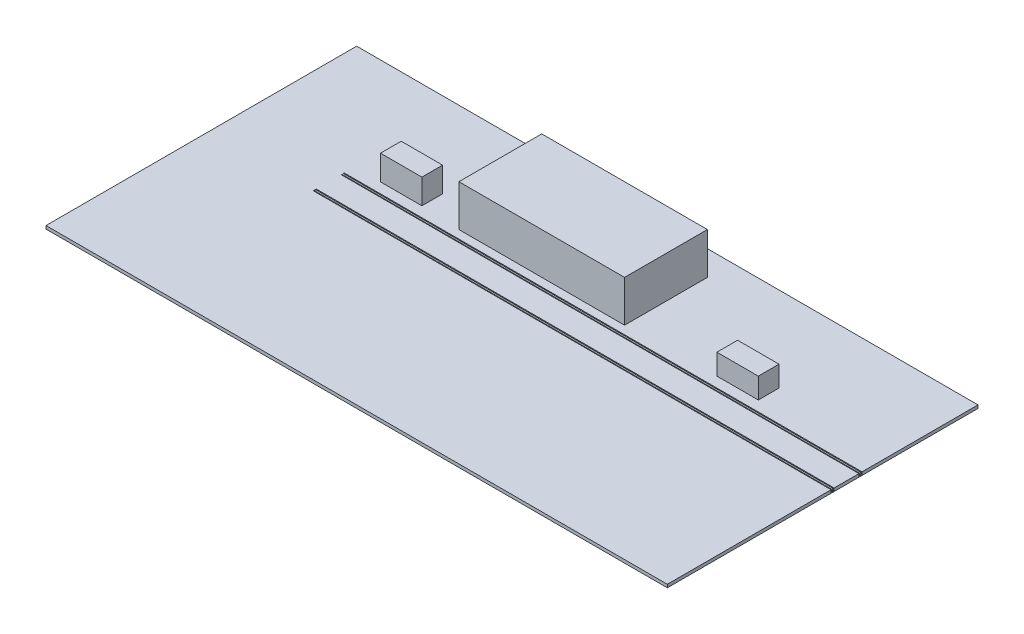
SolidWorks part; units mm, degrees
ref_plane "Front Plane" through (0, 0, 0) normal (0, 0, 1) x (1, 0, 0)
ref_plane "Top Plane" through (0, 0, 0) normal (0, 1, 0) x (1, 0, 0)
ref_plane "Right Plane" through (0, 0, 0) normal (1, 0, 0) x (0, 0, -1)
sketch "Sketch1" plane through (0, 0, 0) normal (0, 1, 0) x (1, 0, 0)
  line L1 (0, 0) -> (30000, 0)
  line L2 (0, 0) -> (0, 15000)
  line L3 (0, 15000) -> (30000, 15000)
  line L4 (30000, 0) -> (30000, 15000)
  dimension "D1" = 30000
  dimension "D2" = 15000
extrude "Boss-Extrude3" add sketch "Sketch1" along normal blind 150
ref_plane "Plane1" through (5000, 0, 0) normal (-1, 0, 0) x (0, 0, 1)
sketch "Sketch3" plane through (5000, 0, 0) normal (-1, 0, 0) x (0, 0, 1)
  line L0 (-15000, 150) -> (0, 150) construction
  line L1 (-9400, 150) -> (-7904, 150)
  line L2 (-9400, 150) -> (-9400, 0)
  line L3 (-9400, 0) -> (-7904, 0)
  line L4 (-7904, 150) -> (-7904, 0)
  line L5 (-15000, 0) -> (0, 0) construction
  line L7 (-9385.7322, 9.9989) -> (-9344.9003, 22.6122)
  line L8 (-9337.8517, 32.1667) -> (-9337.8517, 85.4861)
  line L9 (-9345.6022, 95.2298) -> (-9374.9273, 102)
  line L10 (-9374.9273, 102) -> (-9366.7893, 137.2495)
  line L11 (-9357.0456, 145) -> (-9294.9544, 145)
  line L12 (-9285.2107, 137.2495) -> (-9277.0727, 102)
  line L13 (-9314.1483, 85.4861) -> (-9314.1483, 32.1017)
  line L14 (-9307.1803, 22.5725) -> (-9266.1873, 9.5293)
  line L16 (-9306.3978, 95.2298) -> (-9277.0727, 102)
  line L17 (-9326, 145) -> (-9326, 0) construction
  line L18 (-10531.7423, 0) -> (-8120.2577, 0) construction
  line L19 (-9252, 150) -> (-9252, 0)
  line L20 (-15000, 150) -> (-15000, 0) construction
  line L21 (-8052, 150) -> (-8052, 0)
  line L22 (-8652, 150) -> (-8652, 0) construction
  line L23 (-7997.6022, 95.2298) -> (-8026.9273, 102)
  line L24 (-7996.8197, 22.5725) -> (-8037.8127, 9.5293)
  line L25 (-7918.2678, 9.9989) -> (-7959.0997, 22.6122)
  line L26 (-7966.1483, 32.1667) -> (-7966.1483, 85.4861)
  line L27 (-7989.8517, 85.4861) -> (-7989.8517, 32.1017)
  line L28 (-7958.3978, 95.2298) -> (-7929.0727, 102)
  line L29 (-8018.7893, 137.2495) -> (-8026.9273, 102)
  line L30 (-7946.9544, 145) -> (-8009.0456, 145)
  line L31 (-7929.0727, 102) -> (-7937.2107, 137.2495)
  arc A0 (-9266.1873, 9.5293) -> (-9259.2193, 0) centre (-9269.2193, 0) cw
  arc A1 (-9392.7708, 0) -> (-9385.7322, 9.9989) centre (-9382.7807, 0.4443) cw
  arc A2 (-9314.1483, 32.1017) -> (-9307.1803, 22.5725) centre (-9304.1483, 32.1017) ccw
  arc A3 (-9337.8517, 32.1667) -> (-9344.9003, 22.6122) centre (-9347.8517, 32.1667) cw
  arc A4 (-9294.9544, 145) -> (-9285.2107, 137.2495) centre (-9294.9544, 135) cw
  arc A5 (-9357.0456, 145) -> (-9366.7893, 137.2495) centre (-9357.0456, 135) ccw
  arc A6 (-9314.1483, 85.4861) -> (-9306.3978, 95.2298) centre (-9304.1483, 85.4861) cw
  arc A7 (-9337.8517, 85.4861) -> (-9345.6022, 95.2298) centre (-9347.8517, 85.4861) ccw
  arc A8 (-8037.8127, 9.5293) -> (-8044.7807, 0) centre (-8034.7807, 0) ccw
  arc A9 (-7989.8517, 32.1017) -> (-7996.8197, 22.5725) centre (-7999.8517, 32.1017) cw
  arc A10 (-7911.2292, 0) -> (-7918.2678, 9.9989) centre (-7921.2193, 0.4443) ccw
  arc A11 (-7966.1483, 32.1667) -> (-7959.0997, 22.6122) centre (-7956.1483, 32.1667) ccw
  arc A12 (-7989.8517, 85.4861) -> (-7997.6022, 95.2298) centre (-7999.8517, 85.4861) ccw
  arc A13 (-7966.1483, 85.4861) -> (-7958.3978, 95.2298) centre (-7956.1483, 85.4861) cw
  arc A14 (-7946.9544, 145) -> (-7937.2107, 137.2495) centre (-7946.9544, 135) cw
  arc A15 (-8009.0456, 145) -> (-8018.7893, 137.2495) centre (-8009.0456, 135) ccw
  point P16 (-15000, 75)
  point P31 (-9259.2193, 7.3122)
  point P34 (-9392.7807, 7.3122)
  point P37 (-9314.1483, 24.7895)
  point P40 (-9337.8517, 24.7895)
  point P43 (-9287, 145)
  point P46 (-9365, 145)
  point P49 (-9314.1483, 93.4404)
  point P52 (-9337.8517, 93.4404)
  point P59 (-8044.7807, 7.3122)
  point P64 (-7989.8517, 24.7895)
  point P70 (-7911.2193, 7.3122)
  point P72 (-7966.1483, 24.7895)
  point P77 (-7989.8517, 93.4404)
  point P81 (-7966.1483, 93.4404)
  point P89 (-8017, 145)
  point P90 (-7939, 145)
  dimension "D9" = 10
  dimension "D1" = 1496
  dimension "D2" = 43
  dimension "D3" = 145
  dimension "D4" = 78
  dimension "D5" = 35
  dimension "D6" = 26
  dimension "D7" = 35
  dimension "D8" = 5600
  dimension "D10" = 1200
extrude "Cut-Extrude1" cut sketch "Sketch3" against normal blind 150000
ref_plane "Plane2" through (0, 0, -8652) normal (0, 0, 1) x (1, 0, 0)
mirror "Mirror1" about plane through (0, 0, -8652) normal (0, 0, 1) of "Cut-Extrude1"
sketch "Sketch4" plane through (0, 150, 0) normal (0, 1, 0) x (1, 0, 0)
  line L0 (30000, 9400) -> (5000, 9400) construction
  line L1 (6249.2383, 10900) -> (8249.2383, 10900)
  line L2 (6249.2383, 10900) -> (6249.2383, 9900)
  line L3 (6249.2383, 9900) -> (8249.2383, 9900)
  line L4 (8249.2383, 10900) -> (8249.2383, 9900)
  dimension "D1" = 500
  dimension "D2" = 2000
  dimension "D3" = 1000
extrude "Boss-Extrude4" add sketch "Sketch4" along normal blind 1200
sketch "Sketch7" plane through (0, 150, 0) normal (0, 1, 0) x (1, 0, 0)
  line L0 (30000, 9400) -> (5000, 9400) construction
  line L1 (22492.4395, 10900) -> (24492.4395, 10900)
  line L2 (22492.4395, 10900) -> (22492.4395, 9900)
  line L3 (22492.4395, 9900) -> (24492.4395, 9900)
  line L4 (24492.4395, 10900) -> (24492.4395, 9900)
  dimension "D1" = 500
  dimension "D2" = 1000
  dimension "D3" = 2000
extrude "Boss-Extrude5" add sketch "Sketch7" along normal blind 1000
sketch "Sketch8" plane through (0, 150, 0) normal (0, 1, 0) x (1, 0, 0)
  line L0 (30000, 9400) -> (5000, 9400) construction
  line L1 (10135.6688, 13800) -> (18135.6688, 13800)
  line L2 (10135.6688, 13800) -> (10135.6688, 9800)
  line L3 (10135.6688, 9800) -> (18135.6688, 9800)
  line L4 (18135.6688, 13800) -> (18135.6688, 9800)
  dimension "D1" = 400
  dimension "D2" = 4000
  dimension "D3" = 8000
extrude "Boss-Extrude6" add sketch "Sketch8" along normal blind 2000
